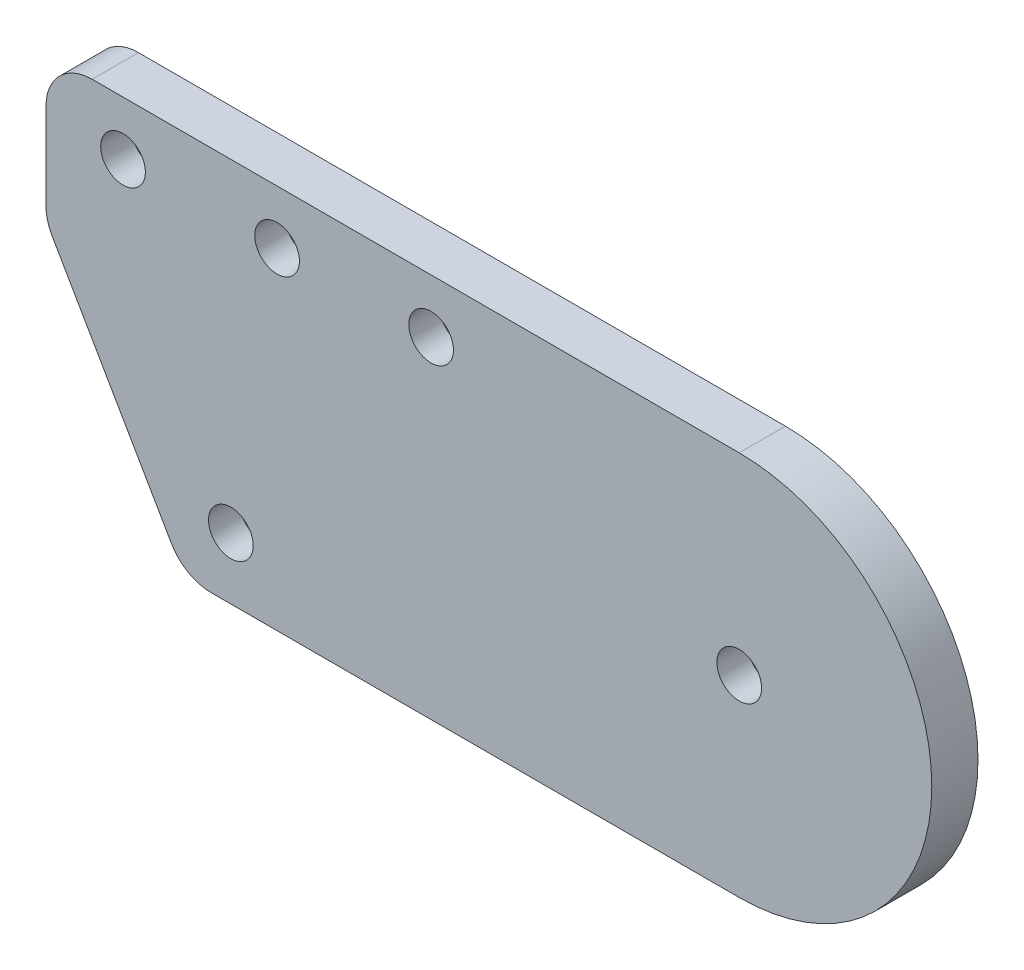
SolidWorks part; units mm, degrees
material "Thornel Mat VMA"
ref_plane "前视基准面" through (0, 0, 0) normal (0, 0, 1) x (1, 0, 0)
ref_plane "上视基准面" through (0, 0, 0) normal (0, 1, 0) x (1, 0, 0)
ref_plane "右视基准面" through (0, 0, 0) normal (1, 0, 0) x (0, 0, -1)
sketch "草图1" plane through (0, 0, 0) normal (0, 0, 1) x (1, 0, 0)
  line L0 (-20, -19) -> (20, -19)
  line L1 (-20, -20) -> (20, -20)
  line L2 (-20, -20) -> (-20, 20)
  line L3 (-20, 20) -> (20, 20)
  line L4 (20, -20) -> (20, 20)
  line L5 (-20, -20) -> (20, 20) construction
  line L6 (-20, 20) -> (20, -20) construction
  line L7 (-20, 15) -> (20, 15) construction
  line L8 (-20, 15) -> (-20, -5) construction
  line L9 (-20, -5) -> (20, -5) construction
  line L10 (20, 15) -> (20, -5) construction
  line L11 (-20, 25) -> (20, 25) construction
  line L12 (-20, 25) -> (-20, -35) construction
  line L13 (-20, -35) -> (20, -35) construction
  line L14 (20, 25) -> (20, -35) construction
  line L15 (-20, -34) -> (20, -34) construction
  line L16 (-20, -19.5) -> (20, -19.5)
  line L17 (-20, -7.89) -> (20, -7.89)
  line L18 (-20, -5.5) -> (20, -5.5)
  line L19 (-20, -33.5) -> (20, -33.5) construction
  line L20 (-20, -31.1) -> (20, -31.1) construction
  circle A0 centre (35, -19.5) radius 12.5
  point P0 (0, 0)
  dimension "D5" = 25
  dimension "D6" = 15
  dimension "D1" = 40
  dimension "D2" = 40
  dimension "D3" = 20
  dimension "D4" = 5
  dimension "D7" = 60
  dimension "D8" = 5
  dimension "D9" = 1
  dimension "D10" = 1
  dimension "D11" = 0.5
  dimension "D12" = 14
  dimension "D13" = 2.39
  dimension "D14" = 14
  dimension "D15" = 2.4
sketch "草图2" plane through (0, 0, 0) normal (0, 0, 1) x (1, 0, 0)
  line L0 (-10, -7) -> (-10, -16.4236)
  line L4 (-20, -20) -> (20, -20) construction
  line L5 (-10, -16.4236) -> (30.7247, -31.2462)
  line L6 (-10, -7) -> (35, -7)
  line L7 (-10, -10.5) -> (20, -10.5) construction
  line L8 (20, -20) -> (20, 20) construction
  line L9 (-10, -10.5) -> (20, -10.5) construction
  line L10 (-10, -16) -> (20, -16) construction
  line L11 (-20, -5.5) -> (20, -5.5) construction
  circle A0 centre (35, -19.5) radius 1.45
  circle A1 centre (35, -19.5) radius 12.5 construction
  arc A2 (35, -7) -> (30.7247, -31.2462) centre (35, -19.5) cw
  circle A3 centre (15, -10.5) radius 1.45
  circle A4 centre (5, -10.5) radius 1.45
  circle A5 centre (-5, -10.5) radius 1.45
  dimension "D3" = 5
  dimension "D7" = 20
  dimension "D8" = 15
  dimension "D9" = 10
  dimension "D11" = 45
  dimension "D12" = 2.9
  dimension "D2" = 5
  dimension "D5" = 4
  dimension "D6" = 9.5
extrude "凸台-拉伸1" add sketch "草图2" along normal blind 3
sketch "草图3" plane through (0, 0, 3) normal (0, 0, 1) x (1, 0, 0)
  line L0 (-10, -16.4236) -> (-10, -32) construction
  line L1 (-10, -32) -> (32.7959, -32) construction
  line L2 (-10, -16.4236) -> (30.7247, -31.2462) construction
  line L3 (-20, -34) -> (20, -34) construction
  line L4 (-10, -16.4236) -> (32.7959, -32)
  line L5 (-10, -28) -> (21.806, -28) construction
  line L6 (-10, -16.4236) -> (-1.0069, -32)
  line L7 (-1.0069, -32) -> (32.7959, -32)
  circle A0 centre (2, -28) radius 1.45
  dimension "D3" = 2.9
  dimension "D4" = 12
  dimension "D1" = 2
  dimension "D2" = 6
  dimension "D5" = 40
extrude "凸台-拉伸2" add sketch "草图3" against normal blind 3
sketch "草图5" plane through (0, 0, 3) normal (0, 0, 1) x (1, 0, 0)
  circle A0 centre (-5, -10.5) radius 3.05
  circle A1 centre (5, -10.5) radius 3.05
  circle A2 centre (15, -10.5) radius 3.05
  dimension "D1" = 6.1
  dimension "D2" = 6.1
  dimension "D3" = 6.1
extrude "切除-拉伸1" [suppressed] cut sketch "草图5" against normal blind 1
sketch "草图6" plane through (0, 0, 0) normal (0, 0, -1) x (-1, 0, 0)
  circle A0 centre (-15, -10.5) radius 3
  circle A1 centre (-5, -10.5) radius 3
  circle A2 centre (5, -10.5) radius 3
  dimension "D1" = 6
extrude "切除-拉伸2" cut sketch "草图6" against normal blind 1
sketch "草图7" plane through (0, 0, 3) normal (0, 0, 1) x (1, 0, 0)
  circle A0 centre (2, -28) radius 3.05
  dimension "D1" = 6.1
sketch "草图8" plane through (0, 0, 3) normal (0, 0, 1) x (1, 0, 0)
  line L0 (32.7959, -32) -> (35, -32)
  line L1 (35, -32) -> (30.7247, -31.2462)
  line L2 (30.7247, -31.2462) -> (32.7959, -32)
  arc A0 (30.7247, -31.2462) -> (35, -7) centre (35, -19.5) ccw construction
extrude "凸台-拉伸3" add sketch "草图8" against normal blind 3
extrude "切除-拉伸4" [suppressed] cut sketch "草图7" against normal blind 1
sketch "草图9" plane through (0, 0, 0) normal (0, 0, -1) x (-1, 0, 0)
  circle A0 centre (-2, -28) radius 3.05
  dimension "D1" = 6.1
extrude "切除-拉伸5" cut sketch "草图9" against normal blind 1
fillet "圆角1" radius 3 3 edges at (-10, -7, 1.5) (-10, -16.4236, 1.5) (-1.0069, -32, 1.5)
sketch "草图10" plane through (0, 0, 3) normal (0, 0, 1) x (1, 0, 0)
  circle A0 centre (35, -19.5) radius 3.05
  dimension "D1" = 6.1
extrude "切除-拉伸6" [suppressed] cut sketch "草图10" against normal blind 1
sketch "草图11" plane through (0, 0, 0) normal (0, 0, -1) x (-1, 0, 0)
  circle A0 centre (-35, -19.5) radius 3.05
  dimension "D1" = 6.1
extrude "切除-拉伸7" cut sketch "草图11" against normal blind 1
